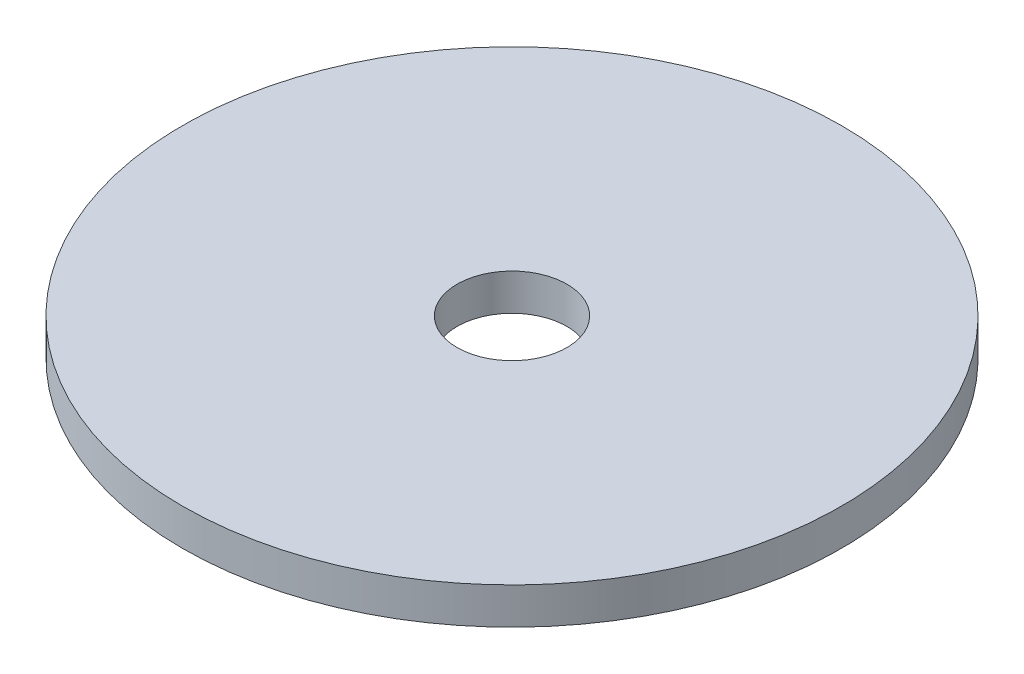
SolidWorks part; units mm, degrees
ref_plane "Спереди" through (0, 0, 0) normal (0, 0, 1) x (1, 0, 0)
ref_plane "Сверху" through (0, 0, 0) normal (0, 1, 0) x (1, 0, 0)
ref_plane "Справа" through (0, 0, 0) normal (1, 0, 0) x (0, 0, -1)
sketch "Эскиз1" plane through (0, 0, 0) normal (0, 1, 0) x (1, 0, 0)
  circle A0 centre (0, 0) radius 36
  circle A1 centre (0, 0) radius 6
extrude "Вытянуть1" add sketch "Эскиз1" along normal blind 4
